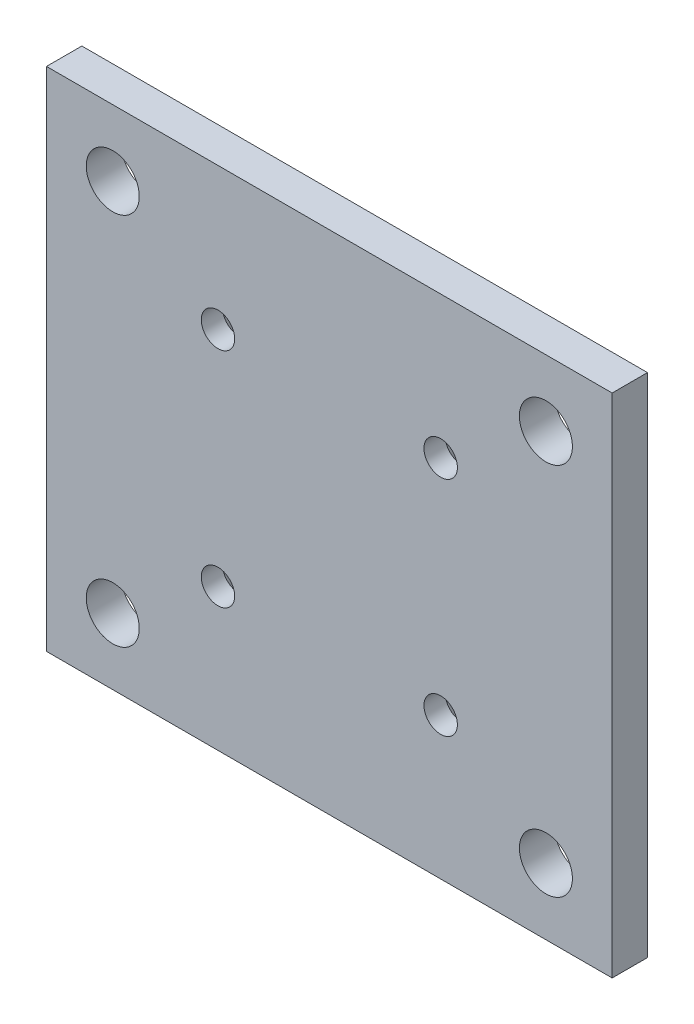
SolidWorks part; units mm, degrees
ref_plane "Front Plane" through (0, 0, 0) normal (0, 0, 1) x (1, 0, 0)
ref_plane "Top Plane" through (0, 0, 0) normal (0, 1, 0) x (1, 0, 0)
ref_plane "Right Plane" through (0, 0, 0) normal (1, 0, 0) x (0, 0, -1)
ref_plane "Plane1" through (6, 10.7709, -46.1) normal (0, -1, 0) x (-1, 0, 0)
sketch "Sketch2" plane through (0, 0, -51.1) normal (0, 0, -1) x (-1, 0, 0)
  line L0 (0, 388.7269) -> (0, 343.2269) construction
  line L1 (13.5, 388.7269) -> (25.4, 388.7269)
  line L2 (25.4, 388.7269) -> (25.4, 343.2269)
  line L3 (25.4, 343.2269) -> (13.5, 343.2269)
  line L4 (-13.5, 343.2269) -> (13.5, 343.2269)
  line L5 (13.5, 343.2269) -> (13.5, 388.7269)
  line L6 (13.5, 388.7269) -> (-13.5, 388.7269)
  line L7 (-13.5, 388.7269) -> (-13.5, 343.2269)
  line L8 (-13.5, 343.2269) -> (13.5, 343.2269)
  line L9 (13.5, 343.2269) -> (13.5, 388.7269) construction
  line L10 (13.5, 388.7269) -> (-13.5, 388.7269)
  line L11 (-13.5, 388.7269) -> (-13.5, 343.2269) construction
  line L12 (-13.5, 388.7269) -> (-25.4, 388.7269)
  line L13 (-25.4, 388.7269) -> (-25.4, 343.2269)
  line L14 (-25.4, 343.2269) -> (-13.5, 343.2269)
  line L15 (25.4, 365.9769) -> (-25.4, 365.9769) construction
  line L16 (13.5, 388.7269) -> (25.4, 388.7269) construction
  line L17 (13.5, 388.7269) -> (13.5, 376.8269) construction
  line L18 (13.5, 376.8269) -> (25.4, 376.8269) construction
  line L19 (25.4, 388.7269) -> (25.4, 376.8269) construction
  line L20 (13.5, 388.7269) -> (25.4, 376.8269) construction
  line L21 (13.5, 376.8269) -> (25.4, 388.7269) construction
  circle A0 centre (10, 355.9769) radius 1.5 construction
  circle A1 centre (10, 375.9769) radius 1.5 construction
  circle A2 centre (-10, 375.9769) radius 1.5 construction
  circle A3 centre (-10, 355.9769) radius 1.5 construction
  circle A4 centre (10, 355.9769) radius 1.5
  circle A5 centre (10, 375.9769) radius 1.5
  circle A6 centre (-10, 375.9769) radius 1.5
  circle A7 centre (-10, 355.9769) radius 1.5
  circle A8 centre (19.45, 382.7769) radius 2.3813
  circle A9 centre (-19.45, 382.7769) radius 2.3813
  circle A10 centre (19.45, 349.1769) radius 2.3813
  circle A11 centre (-19.45, 349.1769) radius 2.3813
  point P22 (19.45, 382.7769)
  dimension "D3" = 4.7625
  dimension "D2" = 25.4
  dimension "D1" = 0
extrude "Boss-Extrude1" add sketch "Sketch2" along normal blind 3.175
chamfer "Chamfer1" distance 1.27 4 edges at (10, 357.4769, -54.275) (-10, 357.4769, -54.275) (-10, 377.4769, -54.275) (10, 377.4769, -54.275)
